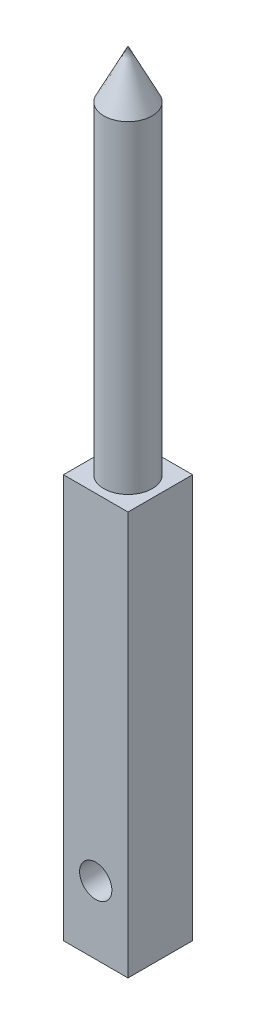
SolidWorks part; units mm, degrees
ref_plane "Plan de face" through (0, 0, 0) normal (0, 0, 1) x (1, 0, 0)
ref_plane "Plan de dessus" through (0, 0, 0) normal (0, 1, 0) x (1, 0, 0)
ref_plane "Plan de droite" through (0, 0, 0) normal (1, 0, 0) x (0, 0, -1)
sketch "Esquisse1" plane through (0, 0, 0) normal (0, 0, 1) x (1, 0, 0)
  line L0 (0, 0) -> (3, 0)
  line L1 (0, 0) -> (0, 6) construction
  line L2 (0, 6) -> (3, 0)
  line L3 (0, 0) -> (0, 6)
revolve "Révolution1" add sketch "Esquisse1" angle 360 about L3
sketch "Esquisse2" plane through (0, 0, 0) normal (0, -1, 0) x (1, 0, 0)
  circle A0 centre (0, 0) radius 3
  point P3 (0, 0)
extrude "Boss.-Extru.1" add sketch "Esquisse2" along normal blind 90
sketch "Esquisse3" plane through (0, -90, 0) normal (0, -1, 0) x (1, 0, 0)
  line L1 (4, -4) -> (-4, -4)
  line L2 (4, -4) -> (4, 4)
  line L3 (4, 4) -> (-4, 4)
  line L4 (-4, -4) -> (-4, 4)
  line L5 (4, -4) -> (-4, 4) construction
  line L6 (4, 4) -> (-4, -4) construction
  circle A0 centre (0, 0) radius 3 construction
  dimension "D1" = 8
  dimension "D2" = 8
extrude "Boss.-Extru.2" add sketch "Esquisse3" against normal blind 50
sketch "Esquisse5" plane through (0, 0, 4) normal (0, 0, 1) x (1, 0, 0)
  circle A0 centre (0, -104.0809) radius 2
  point P6 (0, -104.0809)
sketch "Esquisse8" plane through (0, 0, -4) normal (0, 0, -1) x (-1, 0, 0)
  line L0 (4, -81.5747) -> (-4, -81.5747) construction
  line L1 (4, -40) -> (4, -90) construction
  line L2 (-4, -40) -> (-4, -90) construction
  circle A0 centre (0, -81.5747) radius 2
extrude "Enlèv. mat.-Extru.4" cut sketch "Esquisse8" against normal blind 10
